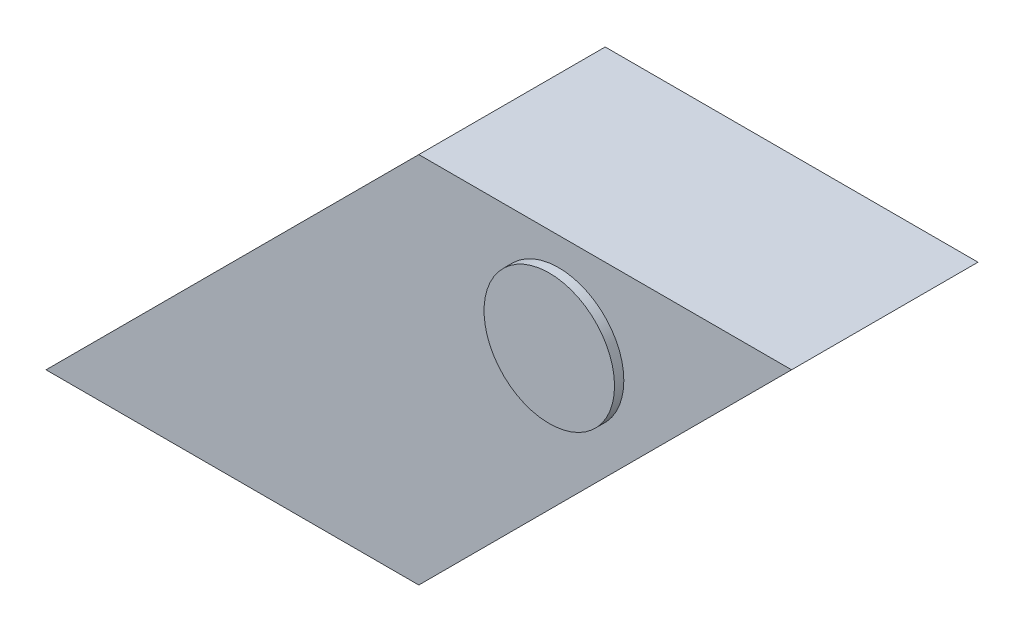
SolidWorks part; units mm, degrees
ref_plane "Plan de face" through (0, 0, 0) normal (0, 0, 1) x (1, 0, 0)
ref_plane "Plan de dessus" through (0, 0, 0) normal (0, 1, 0) x (1, 0, 0)
ref_plane "Plan de droite" through (0, 0, 0) normal (1, 0, 0) x (0, 0, -1)
sketch "Esquisse1" plane through (0, 0, 0) normal (0, 0, 1) x (1, 0, 0)
  line L0 (0, 0) -> (400, 400)
  line L1 (0, 0) -> (400, 0)
  line L2 (400, 400) -> (800, 400)
  line L3 (400, 0) -> (800, 400)
  dimension "D1" = 800
  dimension "D2" = 45
  dimension "D3" = 400
  dimension "D4" = 400
extrude "Boss.-Extru.1" add sketch "Esquisse1" along normal blind 200
sketch "Esquisse2" plane through (0, 0, 200) normal (0, 0, 1) x (1, 0, 0)
  line L0 (800, 400) -> (400, 400) construction
  circle A0 centre (550, 300) radius 70
  dimension "D1" = 100
  dimension "D3" = 140
  dimension "D2" = 550
extrude "Boss.-Extru.2" add sketch "Esquisse2" along normal blind 10
sketch "Esquisse3" plane through (0, 0, 0) normal (0, -1, 0) x (-1, 0, 0)
  line L1 (0, -200) -> (0, 0) construction
  line L2 (0, -200) -> (-400, -200) construction
  circle A0 centre (-200, -100) radius 50
  point P4 (0, 0)
  point P7 (0, 0)
  point P8 (0, 0)
  dimension "D1" = 100
  dimension "D2" = 200
  dimension "D3" = 100
extrude "Enlèv. mat.-Extru.1" cut sketch "Esquisse3" against normal blind 10
